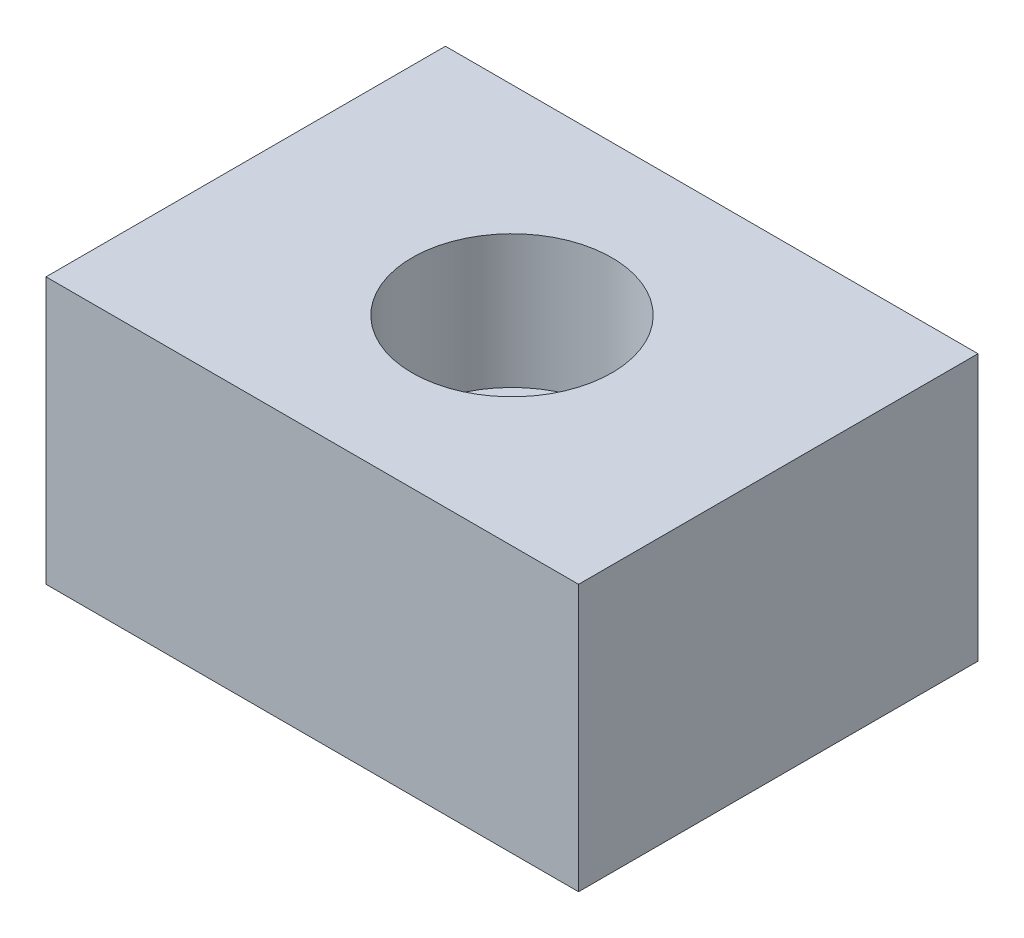
SolidWorks part; units mm, degrees
ref_plane "Front Plane" through (0, 0, 0) normal (0, 0, 1) x (1, 0, 0)
ref_plane "Top Plane" through (0, 0, 0) normal (0, 1, 0) x (1, 0, 0)
ref_plane "Right Plane" through (0, 0, 0) normal (1, 0, 0) x (0, 0, -1)
sketch "Sketch1" plane through (0, 0, 0) normal (0, 1, 0) x (1, 0, 0)
  line L1 (-12.7, -9.525) -> (12.7, -9.525)
  line L2 (-12.7, -9.525) -> (-12.7, 9.525)
  line L3 (-12.7, 9.525) -> (12.7, 9.525)
  line L4 (12.7, -9.525) -> (12.7, 9.525)
  line L5 (-12.7, -9.525) -> (12.7, 9.525) construction
  line L6 (-12.7, 9.525) -> (12.7, -9.525) construction
  point P0 (0, 0)
  dimension "D1" = 25.4
  dimension "D2" = 19.05
extrude "Boss-Extrude1" add sketch "Sketch1" along normal blind 12.7
sketch "Sketch2" plane through (0, 12.7, 0) normal (0, 1, 0) x (1, 0, 0)
  circle A0 centre (0, 0) radius 4.7625
  dimension "D1" = 9.525
extrude "Cut-Extrude1" cut sketch "Sketch2" against normal blind 6.35
sketch "Sketch3" plane through (0, 6.35, 0) normal (0, 1, 0) x (1, 0, 0)
  circle A0 centre (0, 0) radius 3.81
  dimension "D1" = 7.62
extrude "Cut-Extrude2" cut sketch "Sketch3" against normal through all
